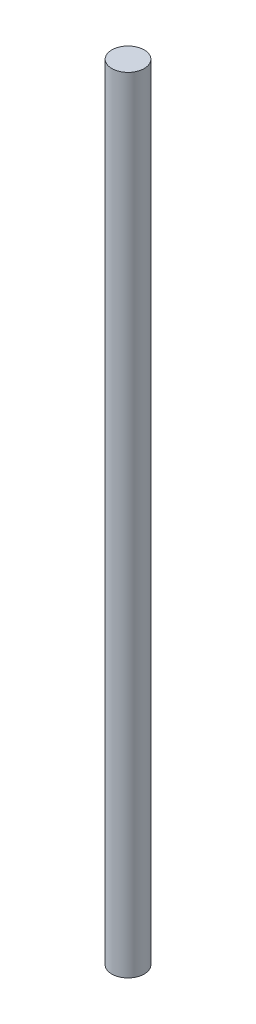
SolidWorks part; units mm, degrees
ref_plane "Front Plane" through (0, 0, 0) normal (0, 0, 1) x (1, 0, 0)
ref_plane "Top Plane" through (0, 0, 0) normal (0, 1, 0) x (1, 0, 0)
ref_plane "Right Plane" through (0, 0, 0) normal (1, 0, 0) x (0, 0, -1)
sketch "Sketch1" plane through (0, 0, 0) normal (0, 1, 0) x (1, 0, 0)
  circle A0 centre (0, 0) radius 4
  dimension "D1" = 8
extrude "Boss-Extrude1" add sketch "Sketch1" along normal blind 194
